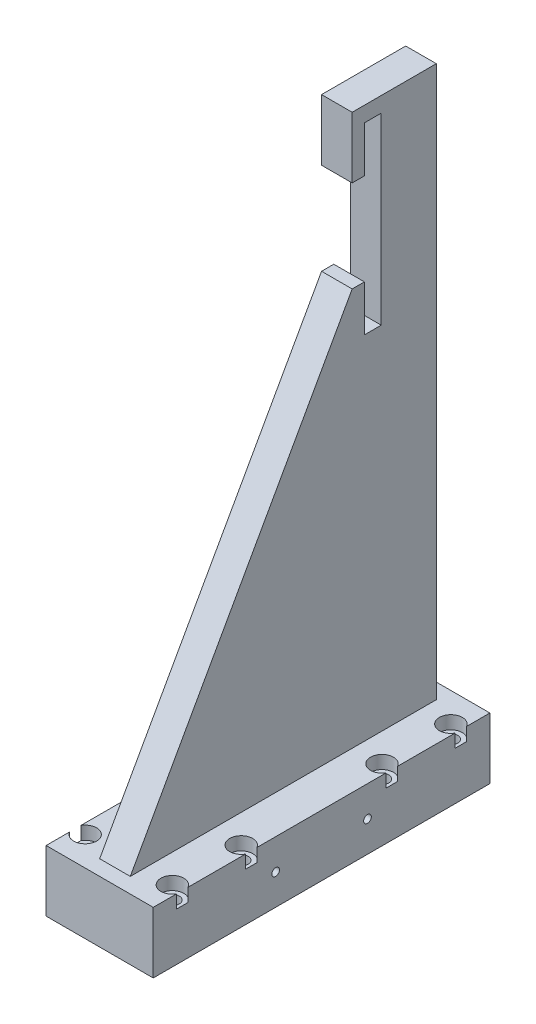
SolidWorks part; units mm, degrees
material "3.1355 (EN-AW 2024)"
ref_plane "Спереди" through (0, 0, 0) normal (0, 0, 1) x (1, 0, 0)
ref_plane "Сверху" through (0, 0, 0) normal (0, 1, 0) x (1, 0, 0)
ref_plane "Справа" through (0, 0, 0) normal (1, 0, 0) x (0, 0, -1)
sketch "Эскиз1" plane through (0, 0, 0) normal (0, 1, 0) x (1, 0, 0)
  line L1 (-35, 110) -> (35, 110)
  line L2 (-35, 110) -> (-35, -110)
  line L3 (-35, -110) -> (35, -110)
  line L4 (35, 110) -> (35, -110)
  point P4 (-35, 0)
  point P6 (0, 110)
  dimension "D1" = 70
  dimension "D2" = 220
extrude "Бобышка-Вытянуть1" add sketch "Эскиз1" along normal blind 40
hole_wizard "Цековка для  винта с внутренним шестигранником M81" positions "Эскиз2" profile "Эскиз3" counterbore size "M8" standard "DIN" end condition through all
sketch "Эскиз2" plane through (0, 40, 0) normal (0, 1, 0) x (1, 0, 0)
  line L0 (-28.5, -46) -> (0, -46) construction
  line L1 (0, -46) -> (28.5, -46) construction
  line L2 (28.5, -46) -> (28.5, -91) construction
  line L3 (-35, -110) -> (35, -110) construction
  point P0 (-28.5, -46)
  point P2 (28.5, -46)
  point P4 (28.5, -91)
  point P6 (-28.5, -91)
  dimension "D1" = 57
  dimension "D2" = 45
  dimension "D3" = 19
sketch "Эскиз3" plane through (-28.5, 40, 46) normal (1, 0, 0) x (0, 0, 1)
  line L0 (0, 0) -> (0, 40)
  line L1 (0, 40) -> (4.5, 40)
  line L3 (4.5, 40) -> (4.5, 8.6)
  line L4 (4.5, 8.6) -> (7.5, 8.6)
  line L5 (7.5, 8.6) -> (7.5, 0)
  line L7 (7.5, 0) -> (0, 0)
  line L11 (0, -6.35) -> (0, 107.95) construction
  dimension "Диаметр сквозного отверстия" = 9
  dimension "Глубина сквозного отверстия" = 40
  dimension "Диаметр цековки" = 15
  dimension "Глубина цековки" = 8.6
mirror "Зеркальное отражение1" about plane through (0, 0, 0) normal (0, 0, 1) of "Цековка для  винта с внутренним шестигранником M81"
sketch "Эскиз4" plane through (0, 0, 0) normal (1, 0, 0) x (0, 0, -1)
  line L0 (100, 40) -> (100, 400)
  line L1 (87.2583, 40) -> (49.7417, 40) construction
  line L2 (100, 400) -> (45, 400)
  line L3 (45, 400) -> (45, 360)
  line L4 (45, 360) -> (53, 360)
  line L5 (53, 360) -> (53, 390)
  line L6 (53, 390) -> (64, 390)
  line L7 (64, 390) -> (64, 270)
  line L9 (-49.7417, 40) -> (-87.2583, 40) construction
  line L10 (-100, 40) -> (100, 40)
  line L11 (100, 40) -> (110, 40) construction
  line L12 (-100, 40) -> (-110, 40) construction
  line L13 (64, 270) -> (53, 270)
  line L14 (53, 270) -> (53, 300)
  line L15 (53, 300) -> (45, 300)
  line L16 (45, 300) -> (-100, 40)
  dimension "D1" = 10
  dimension "D2" = 360
  dimension "D3" = 55
  dimension "D4" = 40
  dimension "D5" = 8
  dimension "D6" = 30
  dimension "D7" = 11
  dimension "D8" = 36
  dimension "D9" = 120
  dimension "D10" = 8
extrude "Бобышка-Вытянуть2" add sketch "Эскиз4" along normal mid plane 20
hole_wizard "Отверстие обработанное метчиком M61" positions "Эскиз5" profile "Эскиз6" tap size "M6" standard "DIN" end condition through all
sketch "Эскиз5" plane through (35, 0, 0) normal (1, 0, 0) x (0, 0, -1)
  line L0 (0, 20) -> (0, 40) construction
  line L1 (-42.2583, 40) -> (42.2583, 40) construction
  line L4 (0, 20) -> (0, 0) construction
  line L7 (-30, 20) -> (0, 20) construction
  line L8 (0, 20) -> (30, 20) construction
  point P2 (-30, 20)
  point P4 (30, 20)
  dimension "D1" = 30
cosmetic thread "Отверстие резьбы1" parameters "D2"=6
cosmetic thread "Отверстие резьбы2" parameters "D2"=6
sketch "Эскиз6" plane through (35, 20, 30) normal (0, 1, 0) x (0, 0, -1)
  line L0 (0, 0) -> (0, 70)
  line L1 (0, 70) -> (2.5, 70)
  line L2 (2.5, 70) -> (2.5, 0)
  line L5 (2.5, 0) -> (0, 0)
  line L11 (0, -6.35) -> (0, 107.95) construction
  dimension "Диаметр проходного сверла" = 5
  dimension "Глубина проходного сверла" = 70
